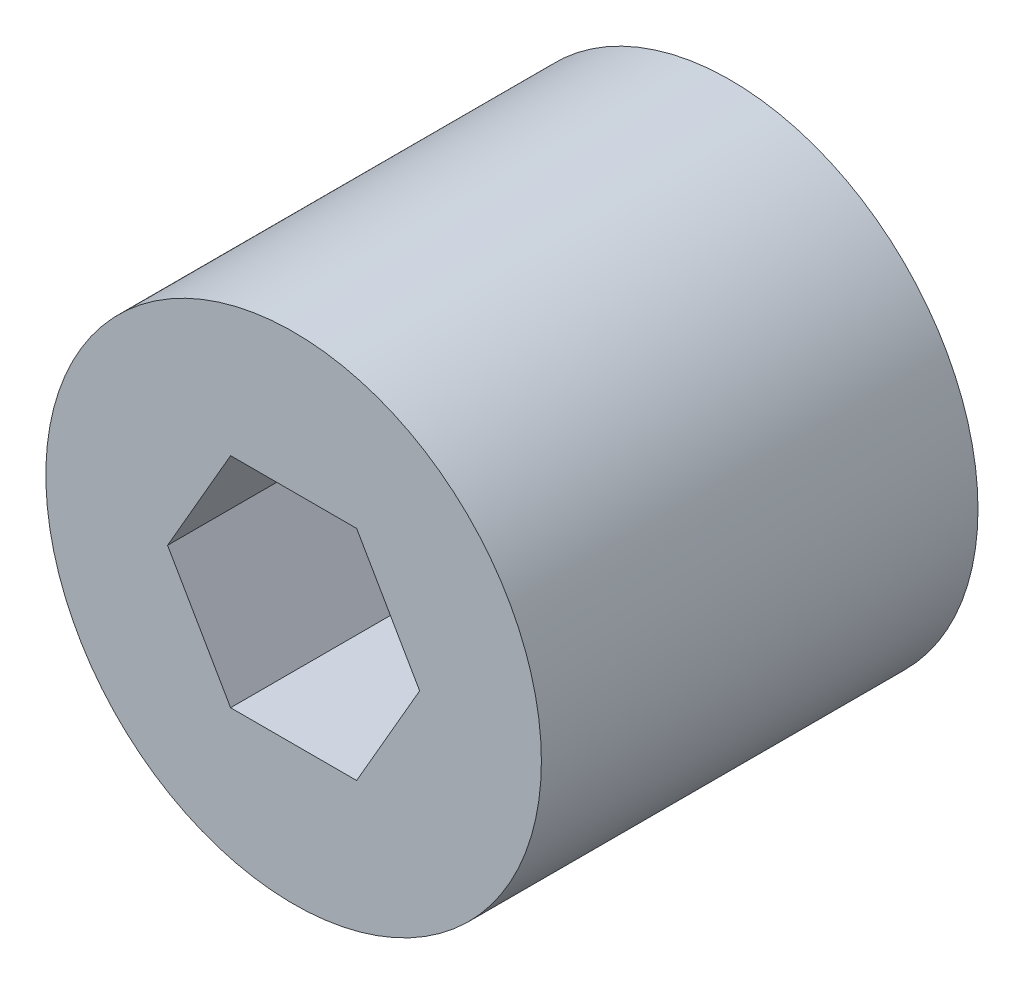
SolidWorks part; units mm, degrees
ref_plane "Front Plane" through (0, 0, 0) normal (0, 0, 1) x (1, 0, 0)
ref_plane "Top Plane" through (0, 0, 0) normal (0, 1, 0) x (1, 0, 0)
ref_plane "Right Plane" through (0, 0, 0) normal (1, 0, 0) x (0, 0, -1)
sketch "Sketch2" plane through (0, 0, 0) normal (0, 0, 1) x (1, 0, 0)
  line L0 (0, 0) -> (16.4829, 0) construction
  line L1 (-3.6662, 6.35) -> (-7.3323, 0)
  line L2 (-7.3323, 0) -> (-3.6662, -6.35)
  line L3 (-3.6662, -6.35) -> (3.6662, -6.35)
  line L4 (3.6662, -6.35) -> (7.3323, 0)
  line L5 (7.3323, 0) -> (3.6662, 6.35)
  line L6 (3.6662, 6.35) -> (-3.6662, 6.35)
  circle A0 centre (0, 0) radius 14.4145
  circle A1 centre (0, 0) radius 6.35 construction
  dimension "D1" = 28.829
  dimension "D2" = 12.7
extrude "Boss-Extrude1" add sketch "Sketch2" against normal blind 25.4
